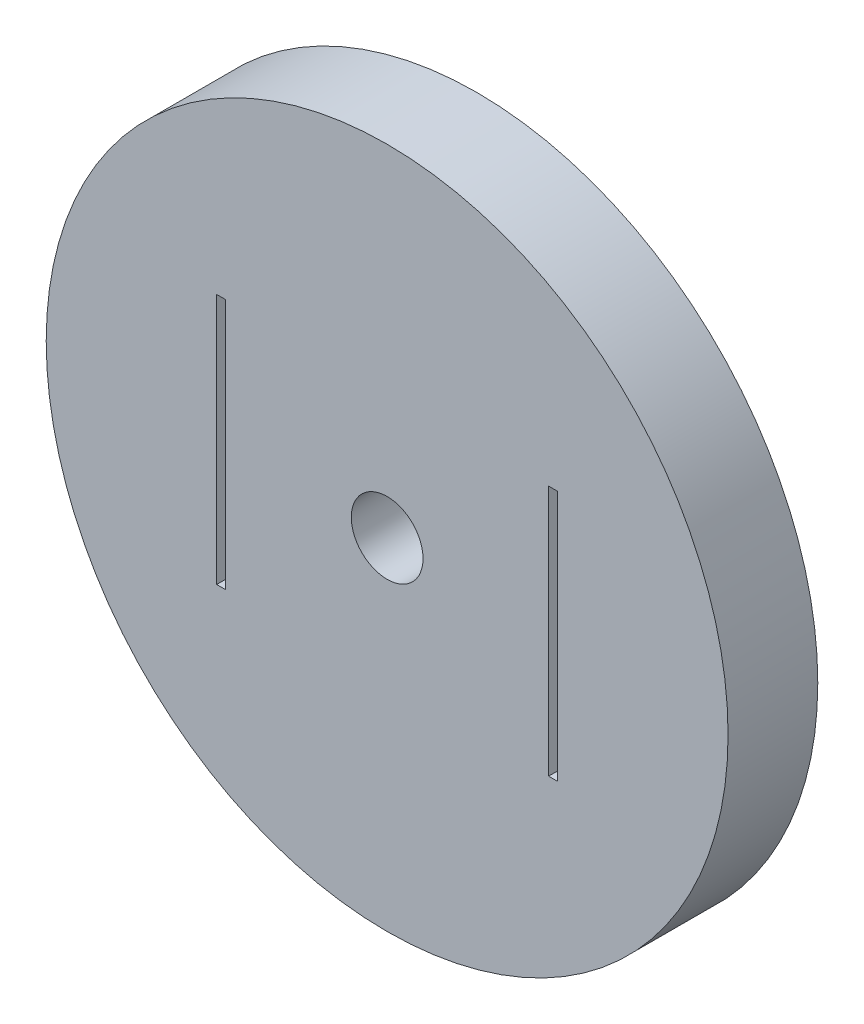
SolidWorks part; units mm, degrees
ref_plane "Front Plane" through (0, 0, 0) normal (0, 0, 1) x (1, 0, 0)
ref_plane "Top Plane" through (0, 0, 0) normal (0, 1, 0) x (1, 0, 0)
ref_plane "Right Plane" through (0, 0, 0) normal (1, 0, 0) x (0, 0, -1)
sketch "Sketch1" plane through (0, 0, 0) normal (0, 0, 1) x (1, 0, 0)
  line L0 (0, 10.3237) -> (0, -11.9962) construction
  line L1 (-9.5, 7) -> (-9, 7)
  line L2 (-9.5, 7) -> (-9.5, -7)
  line L3 (-9.5, -7) -> (-9, -7)
  line L4 (-9, 7) -> (-9, -7)
  line L5 (9, 7) -> (9, -7)
  line L6 (9.5, -7) -> (9, -7)
  line L7 (9.5, 7) -> (9.5, -7)
  line L8 (9.5, 7) -> (9, 7)
  circle A0 centre (0, 0) radius 19
  circle A1 centre (0, 0) radius 2
  dimension "D1" = 4
  dimension "D2" = 38
  dimension "D3" = 0.5
  dimension "D4" = 9
  dimension "D5" = 7
  dimension "D6" = 7
extrude "Boss-Extrude1" add sketch "Sketch1" along normal blind 5
sketch "Sketch3" plane through (0, 0, 0) normal (0, 1, 0) x (1, 0, 0)
  line L0 (-14.5, 6) -> (-14.5, 0) construction
  line L1 (19, 0) -> (-19, 0) construction
  line L2 (-17, 6) -> (-17, 0)
  line L3 (-17, 0) -> (-14.5, 0)
  line L4 (-14.5, 0) -> (-14.5, 8.5)
  line L5 (-19, 0) -> (-19, -5) construction
  circle A0 centre (-14.5, 6) radius 2.5 construction
  arc A1 (-17, 6) -> (-14.5, 8.5) centre (-14.5, 6) cw
  dimension "D1" = 5
  dimension "D2" = 4.5
  dimension "D3" = 8.5
revolve "Revolve1" add sketch "Sketch3" angle 360 about L0
